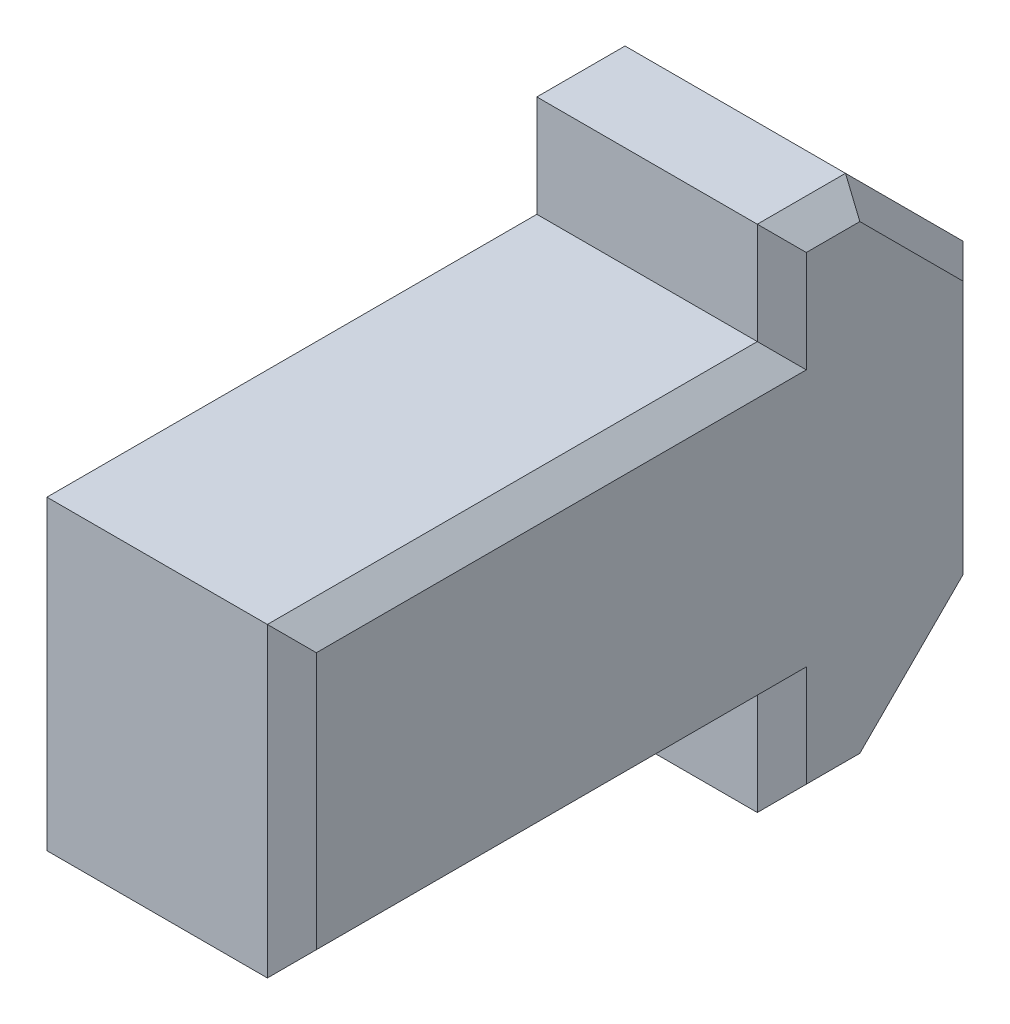
SolidWorks part; units mm, degrees
ref_plane "Front Plane" through (0, 0, 0) normal (0, 0, 1) x (1, 0, 0)
ref_plane "Top Plane" through (0, 0, 0) normal (0, 1, 0) x (1, 0, 0)
ref_plane "Right Plane" through (0, 0, 0) normal (1, 0, 0) x (0, 0, -1)
sketch "Sketch2" plane through (0, 0, 0) normal (1, 0, 0) x (0, 0, -1)
  line L0 (-4.2, 3.125) -> (-14.2, 3.125)
  line L1 (-14.2, 3.125) -> (-14.2, -3.125)
  line L2 (-14.2, -3.125) -> (-4.2, -3.125)
  line L3 (-4.2, 3.125) -> (-4.2, 5.2)
  line L4 (-4.2, 5.2) -> (-2.4, 5.2)
  line L5 (-4.2, -3.125) -> (-4.2, -5.2)
  line L6 (-4.2, -5.2) -> (-2.4, -5.2)
  line L7 (-14.2, 0) -> (0, 0) construction
  line L8 (0, 2.8) -> (0, -2.8)
  line L9 (-2.4, 5.2) -> (0, 2.8)
  line L10 (-2.4, -5.2) -> (0, -2.8)
  point P12 (0, 0)
  dimension "D1" = 6.25
  dimension "D2" = 10.4
  dimension "D3" = 5.2
  dimension "D4" = 1.8
  dimension "D5" = 4.2
  dimension "D6" = 4.2
  dimension "D7" = 5.6
  dimension "D8" = 10
extrude "Boss-Extrude1" add sketch "Sketch2" along normal blind 5
chamfer "Chamfer1" distance 0.5 angle 45 10 edges at (5, 5.2, 3.3) (5, 4, 1.2) (5, 0, 0) (5, -4, 1.2) (5, -5.2, 3.3) (5, -4.1625, 4.2) (5, -3.125, 9.2) (5, 0, 14.2) (5, 3.125, 9.2) (5, 4.1625, 4.2)
equation "\"D3@Sketch2\"=\"D2@Sketch2\"/2"
equation "\"D6@Sketch2\"=\"D5@Sketch2\""
